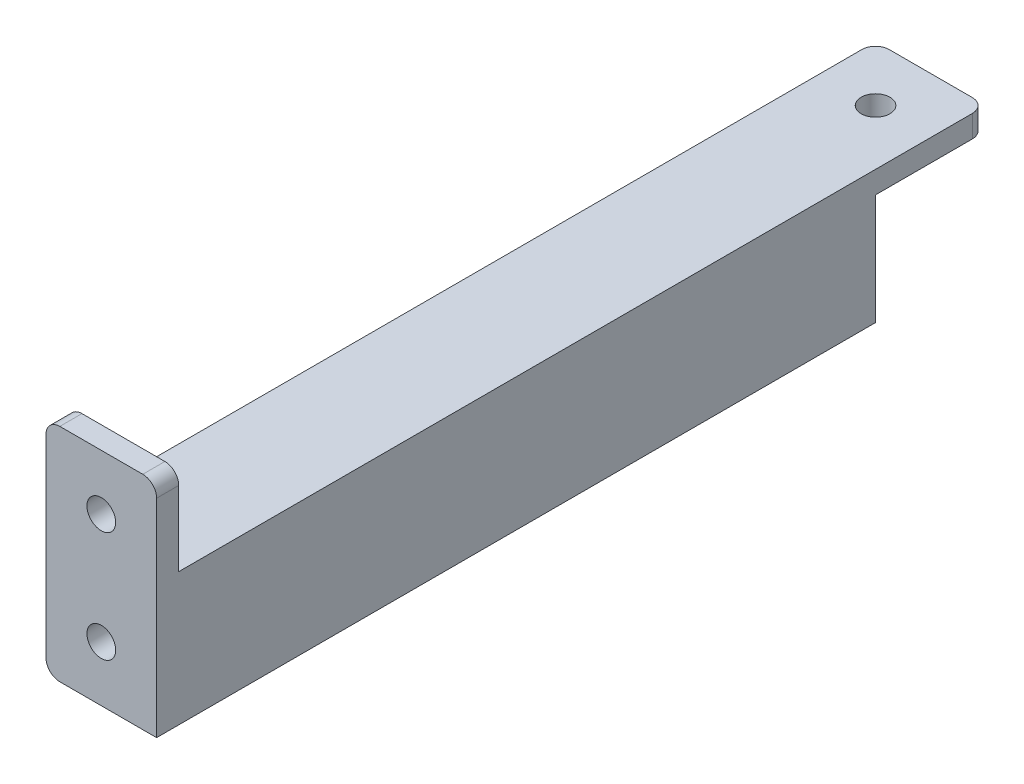
SolidWorks part; units mm, degrees
ref_plane "Спереди" through (0, 0, 0) normal (0, 0, 1) x (1, 0, 0)
ref_plane "Сверху" through (0, 0, 0) normal (0, 1, 0) x (1, 0, 0)
ref_plane "Справа" through (0, 0, 0) normal (1, 0, 0) x (0, 0, -1)
sketch "Эскиз1" plane through (0, 0, 0) normal (0, 0, 1) x (1, 0, 0)
  line L1 (0, 0) -> (20, 0)
  line L2 (0, 0) -> (0, 20)
  line L3 (0, 20) -> (20, 20)
  line L4 (20, 0) -> (20, 20)
  dimension "D1" = 20
  dimension "D2" = 20
extrude "Бобышка-Вытянуть1" add sketch "Эскиз1" along normal blind 4
sketch "Эскиз2" plane through (0, 0, 0) normal (0, 0, 1) x (1, 0, 0)
  line L0 (0, 20) -> (20, 20)
  line L6 (20, 24) -> (0, 24)
  line L7 (0, 24) -> (0, 20)
  line L8 (20, 20) -> (20, 24)
  dimension "D1" = 4
extrude "Бобышка-Вытянуть2" add sketch "Эскиз2" along normal blind 130 and the other way blind 20
sketch "Эскиз3" plane through (0, 0, 0) normal (0, 0, -1) x (-1, 0, 0)
  line L1 (-20, 0) -> (-16, 0)
  line L2 (-20, 0) -> (-20, 24)
  line L3 (-20, 24) -> (-16, 24)
  line L4 (-16, 0) -> (-16, 24)
  dimension "D1" = 4
extrude "Бобышка-Вытянуть3" add sketch "Эскиз3" against normal up to surface (130 mm away) up to face at (10, 22, 130)
sketch "Эскиз4" plane through (0, 0, 130) normal (0, 0, 1) x (1, 0, 0)
  line L0 (0, 24) -> (0, 20) construction
  line L1 (20, 0) -> (0, 0)
  line L2 (20, 0) -> (20, 40)
  line L3 (20, 40) -> (0, 40)
  line L4 (0, 0) -> (0, 40)
  dimension "D1" = 40
extrude "Бобышка-Вытянуть4" add sketch "Эскиз4" against normal blind 4
hole_wizard "Отверстие с зазором M53" positions "Трехмерный эскиз1" profile "Эскиз8" hole size "M5" standard "ISO" end condition through all
sketch3d "Трехмерный эскиз1"
  line L0 (0, 24, -20) -> (0, 24, 126) construction
  line L1 (20, 24, -20) -> (0, 24, -20) construction
  line L2 (0, 20, 4) -> (0, 0, 4) construction
  line L3 (0, 0, 4) -> (16, 0, 4) construction
  line L4 (0, 40, 126) -> (0, 24, 126) construction
  line L6 (0, 0, 126) -> (16, 0, 126) construction
  line L7 (0, 20, 126) -> (0, 0, 126) construction
  point P0 (10, 10, 4)
  point P2 (10, 24, -10)
  point P4 (10, 30, 126)
  point P6 (10, 10, 126)
  dimension "D1" = 10
  dimension "D2" = 10
  dimension "D3" = 10
  dimension "D4" = 10
  dimension "D5" = 10
  dimension "D6" = 10
  dimension "D7" = 10
  dimension "D8" = 10
  dimension "D9" = 20
sketch "Эскиз8" plane through (10, 10, 4) normal (1, 0, 0) x (0, -1, 0)
  line L0 (0, 0) -> (0, 24)
  line L1 (0, 24) -> (2.6, 24)
  line L2 (2.6, 24) -> (2.6, 0)
  line L5 (2.6, 0) -> (0, 0)
  line L11 (0, -6.35) -> (0, 107.95) construction
  dimension "Диаметр сквозного отверстия" = 5.2
  dimension "Глубина сквозного отверстия" = 24
fillet "Скругление1" radius 2.5 6 edges at (0, 0, 2) (0, 0, 128) (20, 40, 128) (0, 40, 128) (20, 22, -20) (0, 22, -20)
mirror "Зеркальное отражение1" [suppressed] about plane through (0, 0, 0) normal (1, 0, 0)
delete or keep bodies "Тело-Удалить/Сохранить 1" [suppressed] type delete bodies bodies 108
